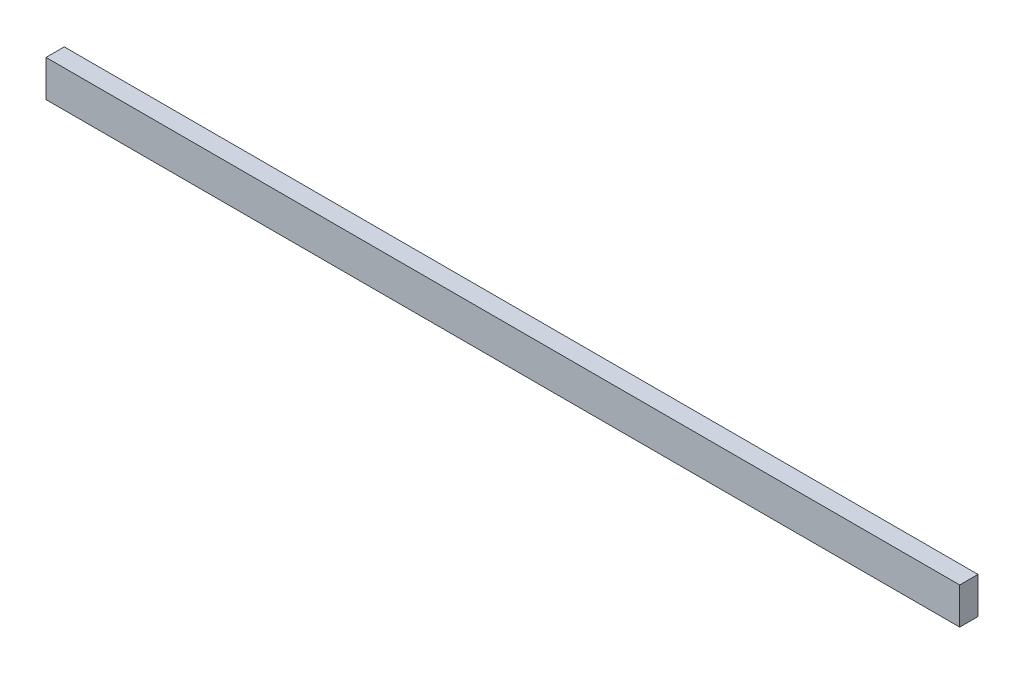
SolidWorks part; units mm, degrees
material "Cast Alloy Steel"
ref_plane "Front Plane" through (0, 0, 0) normal (0, 0, 1) x (1, 0, 0)
ref_plane "Top Plane" through (0, 0, 0) normal (0, 1, 0) x (1, 0, 0)
ref_plane "Right Plane" through (0, 0, 0) normal (1, 0, 0) x (0, 0, -1)
sketch "Sketch1" plane through (0, 0, 0) normal (0, 0, 1) x (1, 0, 0)
  line L1 (0, 0) -> (5000, 0)
  line L2 (0, 0) -> (0, -200)
  line L3 (0, -200) -> (5000, -200)
  line L4 (5000, 0) -> (5000, -200)
  dimension "D1" = 5000
  dimension "D2" = 200
extrude "Boss-Extrude1" add sketch "Sketch1" along normal blind 100
